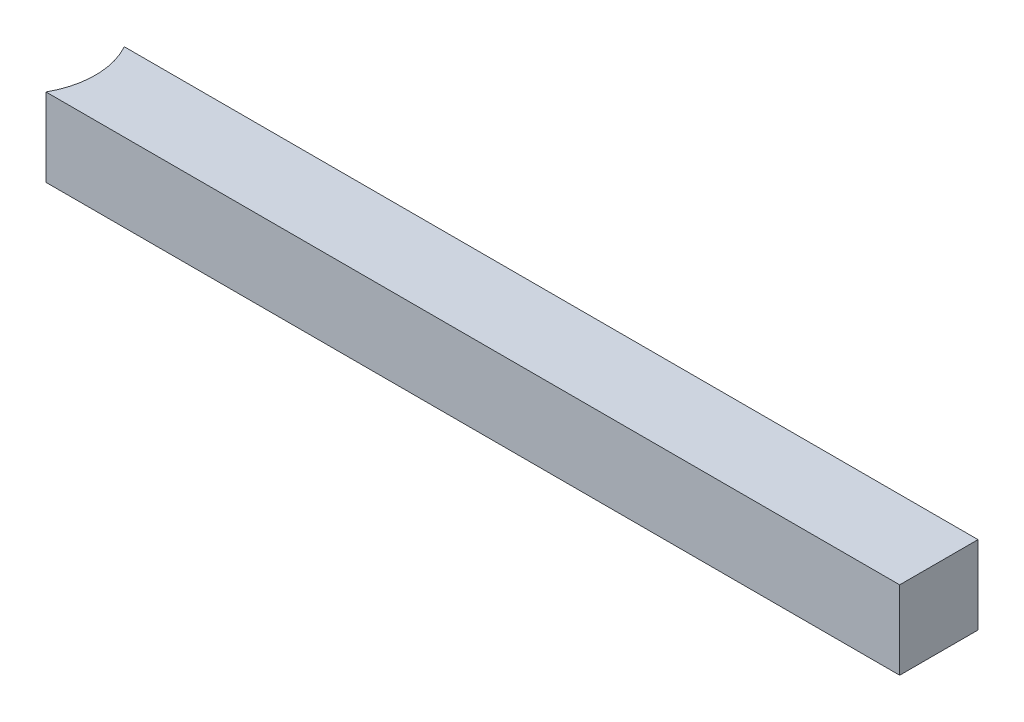
SolidWorks part; units mm, degrees
material "Pine"
ref_plane "X-Y Datum" through (0, 0, 0) normal (0, 0, 1) x (1, 0, 0)
ref_plane "X-Z Datum" through (0, 0, 0) normal (0, 1, 0) x (1, 0, 0)
ref_plane "Y-Z Datum" through (0, 0, 0) normal (1, 0, 0) x (0, 0, -1)
sketch "Sketch1" plane through (0, 0, 0) normal (1, 0, 0) x (0, 0, -1)
  line L1 (-12.7, 12.7) -> (12.7, 12.7)
  line L2 (-12.7, 12.7) -> (-12.7, -12.7)
  line L3 (-12.7, -12.7) -> (12.7, -12.7)
  line L4 (12.7, 12.7) -> (12.7, -12.7)
  line L5 (-12.7, 12.7) -> (12.7, -12.7) construction
  line L6 (-12.7, -12.7) -> (12.7, 12.7) construction
  point P0 (0, 0)
  dimension "D1" = 25.4
extrude "Boss-Extrude1" add sketch "Sketch1" along normal blind 306.07
sketch "Sketch2" plane through (0, 12.7, 0) normal (0, 1, 0) x (1, 0, 0)
  line L0 (306.07, -12.7) -> (0, -12.7) construction
  line L1 (306.07, 12.7) -> (0, 12.7) construction
  line L2 (29.21, -12.7) -> (0, -12.7)
  line L3 (0, -12.7) -> (0, 12.7)
  line L4 (0, 12.7) -> (29.21, 12.7)
  arc A0 (29.21, -12.7) -> (29.21, 12.7) centre (6.4827, 0) ccw
  dimension "D1" = 26.035
  dimension "D2" = 29.21
extrude "Cut-Extrude1" cut sketch "Sketch2" against normal through all both and the other way through all
